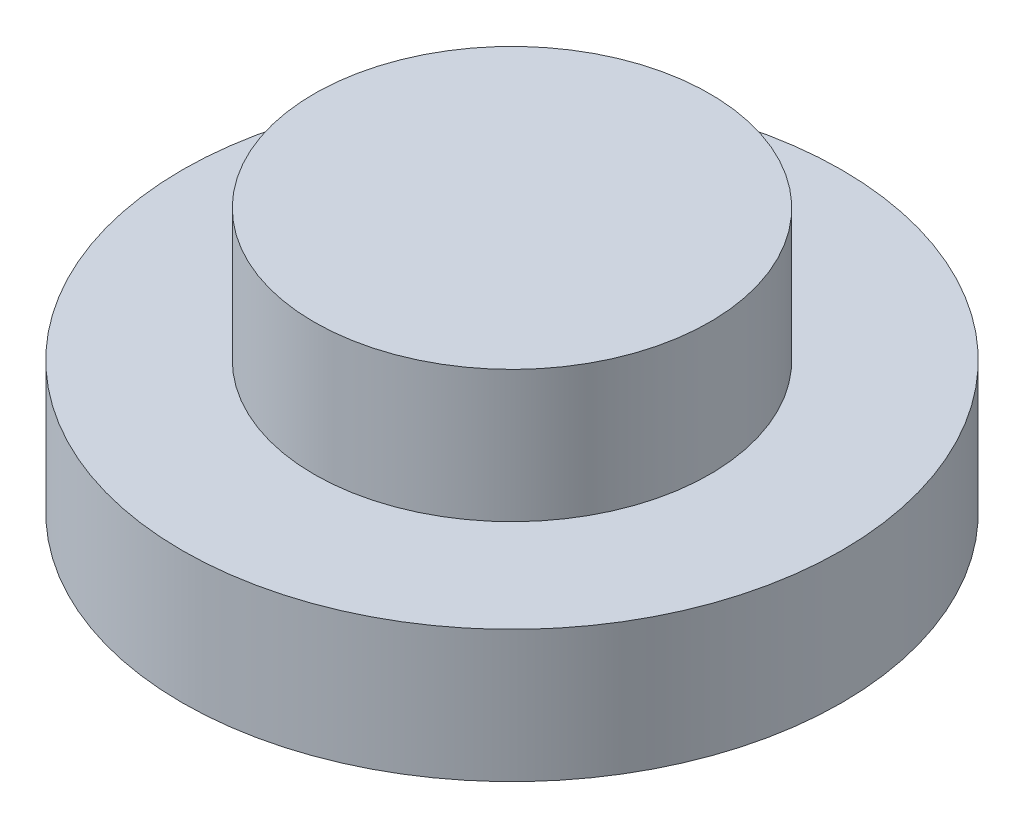
SolidWorks part; units mm, degrees
ref_plane "Front Plane" through (0, 0, 0) normal (0, 0, 1) x (1, 0, 0)
ref_plane "Top Plane" through (0, 0, 0) normal (0, 1, 0) x (1, 0, 0)
ref_plane "Right Plane" through (0, 0, 0) normal (1, 0, 0) x (0, 0, -1)
sketch "Sketch1" plane through (0, 0, 0) normal (0, 1, 0) x (1, 0, 0)
  circle A0 centre (0, 0) radius 25
  dimension "D1" = 50
extrude "Boss-Extrude1" add sketch "Sketch1" along normal blind 10
sketch "Sketch2" plane through (0, 10, 0) normal (0, 1, 0) x (1, 0, 0)
  circle A0 centre (0, 0) radius 15
  dimension "D1" = 30
extrude "Boss-Extrude2" add sketch "Sketch2" along normal blind 10
sketch "Sketch3" plane through (0, 0, 0) normal (0, -1, 0) x (1, 0, 0)
  line L1 (-5, 5) -> (5, 5)
  line L2 (-5, 5) -> (-5, -5)
  line L3 (-5, -5) -> (5, -5)
  line L4 (5, 5) -> (5, -5)
  line L5 (-5, 5) -> (5, -5) construction
  line L6 (-5, -5) -> (5, 5) construction
  point P0 (0, 0)
  dimension "D1" = 10
  dimension "D2" = 10
extrude "Boss-Extrude3" add sketch "Sketch3" along normal blind 2
